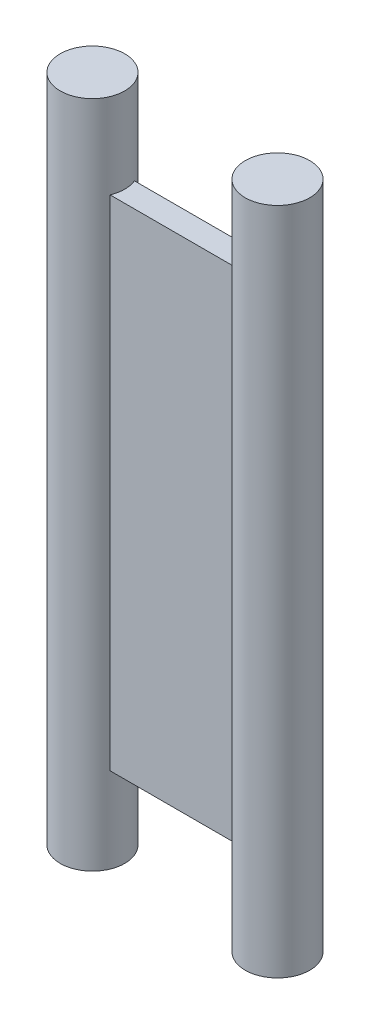
SolidWorks part; units mm, degrees
ref_plane "Front Plane" through (0, 0, 0) normal (0, 0, 1) x (1, 0, 0)
ref_plane "Top Plane" through (0, 0, 0) normal (0, 1, 0) x (1, 0, 0)
ref_plane "Right Plane" through (0, 0, 0) normal (1, 0, 0) x (0, 0, -1)
sketch "Sketch1" plane through (0, 0, 0) normal (0, 1, 0) x (1, 0, 0)
  line L1 (3.803, 0.5) -> (-3.803, 0.5)
  line L2 (3.803, 0.5) -> (3.803, -0.5)
  line L3 (3.803, -0.5) -> (-3.803, -0.5)
  line L4 (-3.803, 0.5) -> (-3.803, -0.5)
  line L5 (3.803, 0.5) -> (-3.803, -0.5) construction
  line L6 (3.803, -0.5) -> (-3.803, 0.5) construction
  point P0 (0, 0)
  dimension "D1" = 7.606
  dimension "D3" = 1
extrude "Boss-Extrude1" add sketch "Sketch1" along normal blind 20.5
ref_plane "Plane1" through (0, 10.25, 0) normal (0, 1, 0) x (1, 0, 0)
sketch "Sketch2" plane through (0, 10.25, 0) normal (0, 1, 0) x (1, 0, 0)
  line L0 (3.803, -0.5) -> (3.803, 0.5) construction
  line L1 (-3.803, 0.5) -> (-3.803, -0.5) construction
  line L2 (3.803, -0.5) -> (3.803, 0.5) construction
  line L3 (-3.803, 0.5) -> (-3.803, -0.5) construction
  circle A0 centre (-3.803, 0) radius 1.325
  circle A1 centre (3.803, 0) radius 1.325
  dimension "D1" = 2.65
extrude "Boss-Extrude2" add sketch "Sketch2" along normal mid plane 27.5
